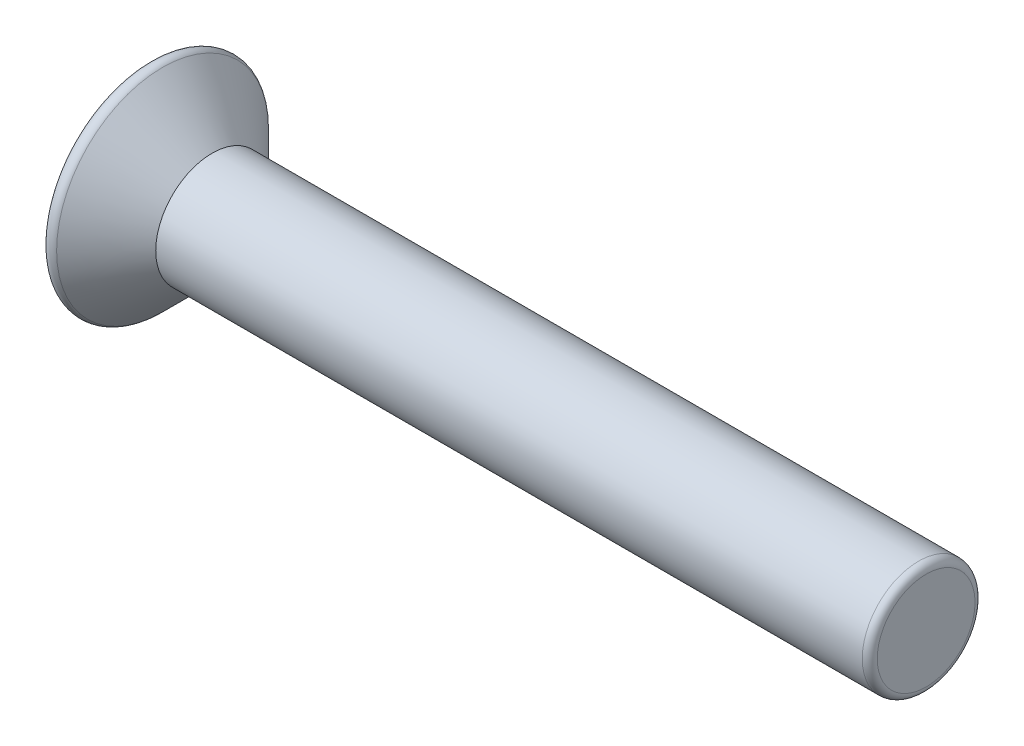
SolidWorks part; units mm, degrees
ref_plane "Plan de face" through (0, 0, 0) normal (0, 0, 1) x (1, 0, 0)
ref_plane "Plan de dessus" through (0, 0, 0) normal (0, 1, 0) x (1, 0, 0)
ref_plane "Plan de droite" through (0, 0, 0) normal (1, 0, 0) x (0, 0, -1)
sketch "Esquisse1" plane through (0, 0, 0) normal (0, 0, 1) x (1, 0, 0)
  line L0 (-5.7689, 0) -> (8.695, 0) construction
  line L1 (0, 0) -> (0, 3.16)
  line L2 (0, 3.16) -> (1.66, 1.5)
  line L3 (1.66, 1.5) -> (20.66, 1.5)
  line L4 (20.66, 1.5) -> (20.66, 0)
  line L5 (0, 0) -> (20.66, 0)
  dimension "D1" = 3.16
  dimension "D2" = 45
  dimension "D3" = 1.66
  dimension "D4" = 19
revolve "Révolution1" add sketch "Esquisse1" angle 360 about L0
sketch "Esquisse2" plane through (0, 0, 0) normal (-1, 0, 0) x (0, 0, 1)
  line L1 (0, -1.1) -> (0.9526, -0.55)
  line L2 (0.9526, -0.55) -> (0.9526, 0.55)
  line L3 (0.9526, 0.55) -> (0, 1.1)
  line L4 (0, 1.1) -> (-0.9526, 0.55)
  line L5 (-0.9526, 0.55) -> (-0.9526, -0.55)
  line L6 (-0.9526, -0.55) -> (0, -1.1)
  circle A0 centre (0, 0) radius 0.9526 construction
  dimension "D1" = 2.2
extrude "Enlèv. mat.-Extru.1" cut sketch "Esquisse2" against normal blind 0.1
fillet "Congé1" radius 0.2 2 edges at (20.66, 0, 1.5) (0, 0, 3.16)
